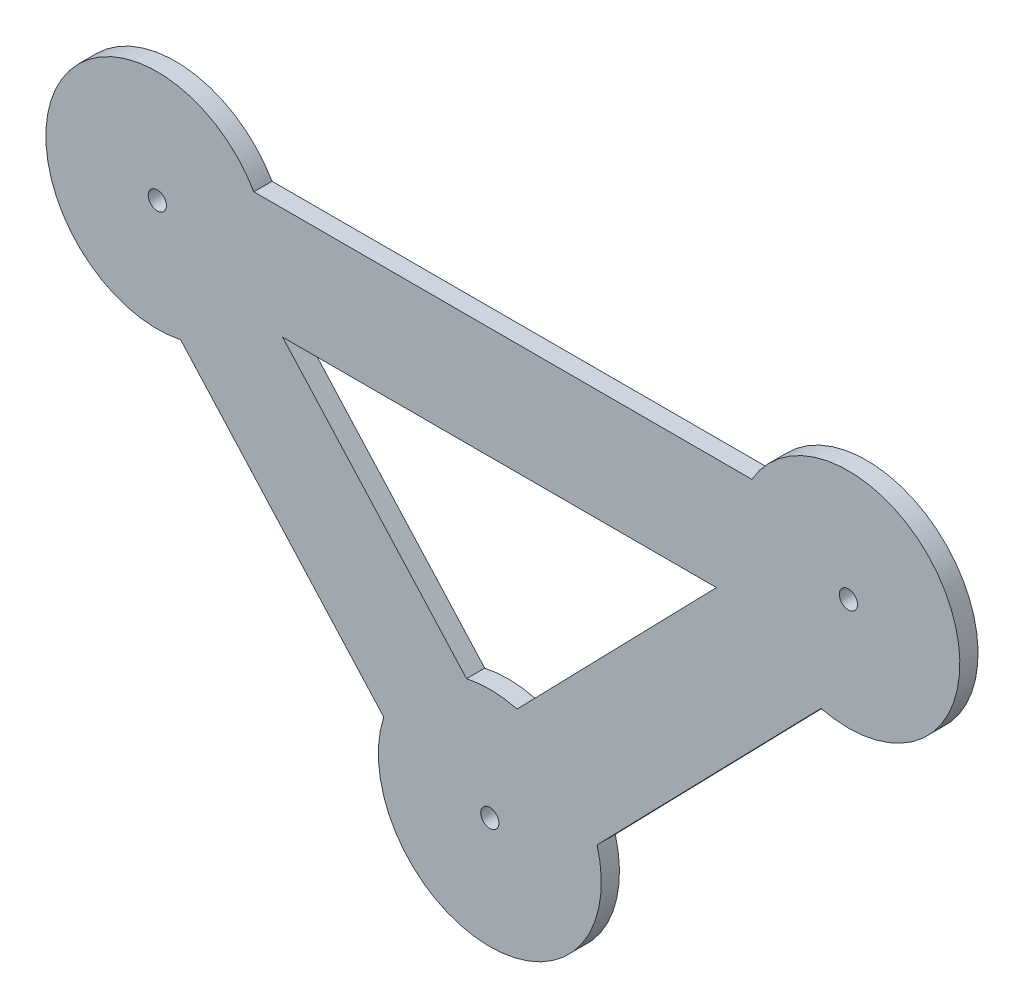
SolidWorks part; units mm, degrees
ref_plane "Front Plane" through (0, 0, 0) normal (0, 0, 1) x (1, 0, 0)
ref_plane "Top Plane" through (0, 0, 0) normal (0, 1, 0) x (1, 0, 0)
ref_plane "Right Plane" through (0, 0, 0) normal (1, 0, 0) x (0, 0, -1)
sketch "Sketch1" plane through (0, 0, 0) normal (0, 0, 1) x (1, 0, 0)
  line L0 (0, 19.05) -> (113.6527, -106.9327) construction
  line L1 (0, 0) -> (236.22, 0)
  line L2 (0, 0) -> (0, 38.1)
  line L3 (0, 38.1) -> (236.22, 38.1)
  line L4 (236.22, 0) -> (236.22, 38.1)
  line L6 (-14.1448, 6.2896) -> (99.5079, -119.6931)
  line L7 (-14.1448, 6.2896) -> (14.1448, 31.8104)
  line L8 (99.5079, -119.6931) -> (127.7975, -94.1723)
  line L9 (113.6527, -106.9327) -> (236.22, 19.05) construction
  line L10 (14.1448, 31.8104) -> (127.7975, -94.1723)
  line L11 (-14.1448, 6.2896) -> (127.7975, -94.1723) construction
  line L12 (99.5079, -119.6931) -> (14.1448, 31.8104) construction
  line L13 (222.5658, 32.334) -> (99.9985, -93.6487)
  line L14 (222.5658, 32.334) -> (249.8742, 5.766)
  line L15 (99.9985, -93.6487) -> (127.3069, -120.2168)
  line L16 (249.8742, 5.766) -> (127.3069, -120.2168)
  line L17 (222.5658, 32.334) -> (127.3069, -120.2168) construction
  line L18 (99.9985, -93.6487) -> (249.8742, 5.766) construction
  circle A0 centre (0, 19.05) radius 3.1115
  circle A1 centre (236.22, 19.05) radius 3.1115
  circle A2 centre (113.6527, -106.9327) radius 3.1115
  circle A3 centre (0, 19.05) radius 38.1
  circle A4 centre (236.22, 19.05) radius 38.1
  circle A5 centre (113.6527, -106.9327) radius 38.1
  point P13 (56.8264, -43.9414)
  point P15 (174.9364, -43.9414)
  dimension "D3" = 6.223
  dimension "D4" = 6.223
  dimension "D11" = 6.223
  dimension "D12" = 76.2
  dimension "D13" = 76.2
  dimension "D14" = 76.2
  dimension "D1" = 236.22
  dimension "D2" = 38.1
  dimension "D5" = 175.768
  dimension "D6" = 169.672
  dimension "D7" = 38.1
  dimension "D8" = 38.1
  dimension "D9" = 19.05
  dimension "D10" = 19.05
extrude "Boss-Extrude1" add sketch "Sketch1" against normal blind 6.223 contours L3 A3 L6 L7 A0 L2 | L10 A3 L3 L2 A0 L7 | L1 A3 L10 L7 A0 L2 | L6 A3 L1 L2 A0 L7 | A4 L3 A3 L10 L1 L13 | A3 L1 L10 | A5 L10 L1 A3 L6 | L3 A4 L13 L14 A1 L4 | A4 L13 L1 | L13 A4 L1 L4 A1 L14 | L16 A4 L3 L4 A1 L14 | L1 A4 L16 L14 A1 L4 | A5 L16 A4 L1 L13 | L13 A5 L10 | L10 A5 L6 L8 A2 L15 L13 | A2 L8 L10 L13 L15 | L16 A5 L13 L10 L8 A2 L15 | L6 A5 L16 L15 A2 L8
